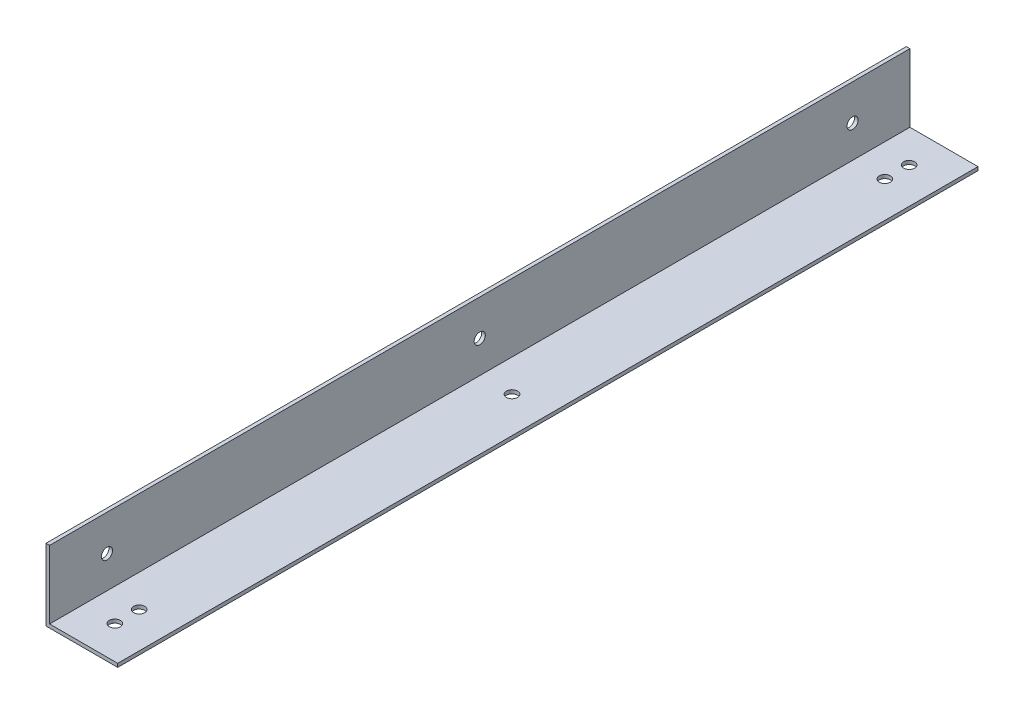
SolidWorks part; units mm, degrees
material "1060 Alloy"
ref_plane "Front Plane" through (0, 0, 0) normal (0, 0, 1) x (1, 0, 0)
ref_plane "Top Plane" through (0, 0, 0) normal (0, 1, 0) x (1, 0, 0)
ref_plane "Right Plane" through (0, 0, 0) normal (1, 0, 0) x (0, 0, -1)
sketch "Sketch2" plane through (0, 0, 0) normal (0, 0, 1) x (1, 0, 0)
  line L0 (0, 0) -> (0, 31.75)
  line L1 (0, 31.75) -> (1.5875, 31.75)
  line L2 (1.5875, 31.75) -> (1.5875, 1.5875)
  line L3 (1.5875, 1.5875) -> (31.75, 1.5875)
  line L4 (31.75, 1.5875) -> (31.75, 0)
  line L5 (31.75, 0) -> (0, 0)
  dimension "D1" = 31.75
  dimension "D2" = 1.5875
  dimension "D3" = 30.1625
  dimension "D4" = 31.75
extrude "Boss-Extrude1" add sketch "Sketch2" along normal blind 381
hole_wizard "#10 (0.1935) Diameter Hole2" positions "Sketch3" profile "Sketch4" hole size "#10" standard "ANSI Inch" end condition through all
sketch "Sketch3" plane through (0, 0, 0) normal (-1, 0, 0) x (0, 0, 1)
  line L0 (190.5, 31.75) -> (190.5, 0) construction
  line L1 (381, 31.75) -> (0, 31.75) construction
  line L2 (381, 0) -> (0, 0) construction
  line L4 (0, 15.875) -> (381, 15.875) construction
  line L5 (0, 31.75) -> (0, 0) construction
  line L6 (381, 31.75) -> (381, 0) construction
  point P17 (25.4, 15.875)
  point P19 (190.5, 15.875)
  point P21 (355.6, 15.875)
  dimension "D1" = 165.1
  dimension "D2" = 165.1
sketch "Sketch4" plane through (0, 15.875, 355.6) normal (0, 1, 0) x (0, 0, 1)
  line L0 (0, 0) -> (0, 31.75)
  line L1 (0, 31.75) -> (2.4574, 31.75)
  line L2 (2.4574, 31.75) -> (2.4574, 0)
  line L5 (2.4574, 0) -> (0, 0)
  line L11 (0, -6.35) -> (0, 107.95) construction
  dimension "Thru Hole Dia." = 4.9149
  dimension "Thru Hole Depth" = 31.75
hole_wizard "#10 (0.1935) Diameter Hole4" positions "Sketch5" profile "Sketch6" hole size "#10" standard "ANSI Inch" end condition through all
sketch "Sketch5" plane through (0, 0, 0) normal (0, -1, 0) x (-1, 0, 0)
  line L0 (0, -190.5) -> (-31.75, -190.5) construction
  line L1 (0, -381) -> (0, 0) construction
  line L2 (-31.75, -381) -> (-31.75, 0) construction
  line L4 (-15.875, 0) -> (-15.875, -381) construction
  line L5 (0, 0) -> (-31.75, 0) construction
  line L6 (0, -381) -> (-31.75, -381) construction
  point P15 (-15.875, -190.5)
  point P17 (-15.875, -25.4)
  point P19 (-15.875, -355.6)
  point P22 (-15.875, -14.605)
  point P24 (-15.875, -366.395)
  dimension "D1" = 165.1
  dimension "D2" = 165.1
  dimension "D3" = 10.795
  dimension "D4" = 10.795
sketch "Sketch6" plane through (15.875, 0, 366.395) normal (1, 0, 0) x (0, 0, -1)
  line L0 (0, 0) -> (0, 31.75)
  line L1 (0, 31.75) -> (2.4574, 31.75)
  line L2 (2.4574, 31.75) -> (2.4574, 0)
  line L5 (2.4574, 0) -> (0, 0)
  line L11 (0, -6.35) -> (0, 107.95) construction
  dimension "Thru Hole Dia." = 4.9149
  dimension "Thru Hole Depth" = 31.75
